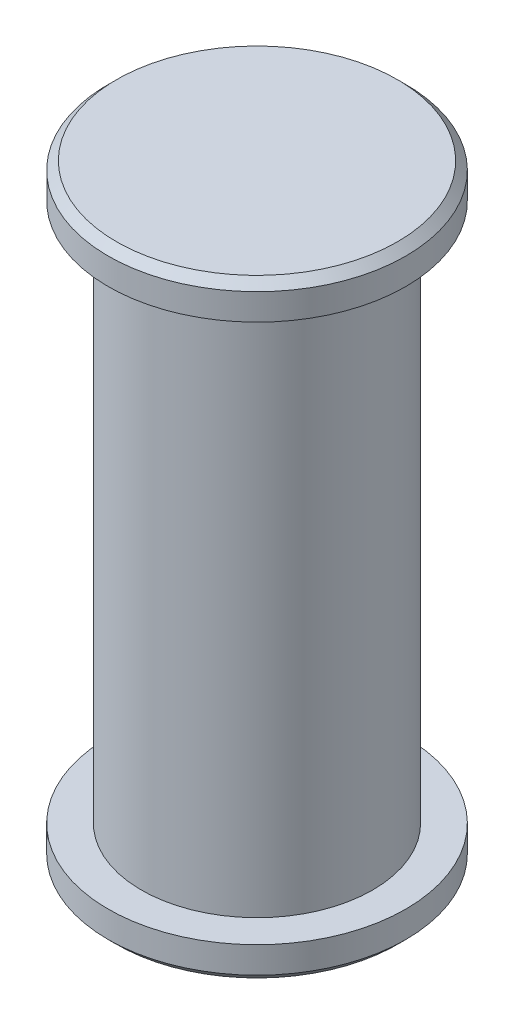
SolidWorks part; units mm, degrees
ref_plane "Front" through (0, 0, 0) normal (0, 0, 1) x (1, 0, 0)
ref_plane "Top" through (0, 0, 0) normal (0, 1, 0) x (1, 0, 0)
ref_plane "Right" through (0, 0, 0) normal (1, 0, 0) x (0, 0, -1)
sketch "Sketch1" plane through (0, 0, 0) normal (0, 0, 1) x (1, 0, 0)
  line L0 (0, 0) -> (0, 18.4078) construction
  line L1 (0, 18.4078) -> (-4.5, 18.4078)
  line L2 (-4.5, 18.4078) -> (-4.5, 17.3589)
  line L3 (-4.5, 17.3589) -> (-3.5, 17.3589)
  line L4 (-3.5, 17.3589) -> (-3.5, 1.0489)
  line L5 (-3.5, 1.0489) -> (-4.5, 1.0489)
  line L6 (-4.5, 1.0489) -> (-4.5, 0)
  line L7 (-4.5, 0) -> (0, 0)
  line L8 (0, 0) -> (0, 18.4078)
  dimension "D1" = 16.31
  dimension "D2" = 3.5
  dimension "D3" = 4.5
revolve "Revolve1" add sketch "Sketch1" angle 360 about L0
chamfer "Chamfer1" distance 0.25 angle 45 2 edges at (4.5, 0, 0) (4.5, 18.4078, 0)
